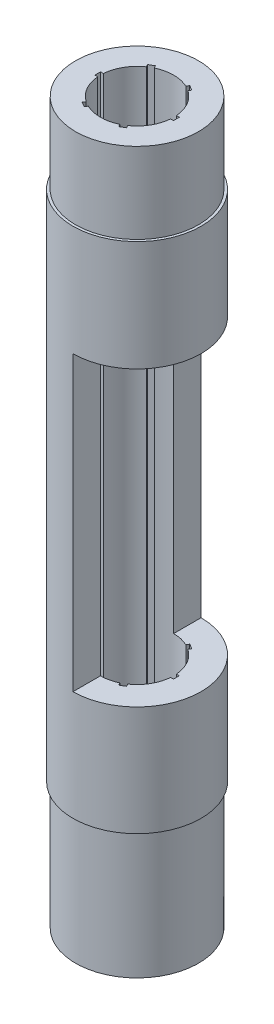
SolidWorks part; units mm, degrees
ref_plane "Front Plane" through (0, 0, 0) normal (0, 0, 1) x (1, 0, 0)
ref_plane "Top Plane" through (0, 0, 0) normal (0, 1, 0) x (1, 0, 0)
ref_plane "Right Plane" through (0, 0, 0) normal (1, 0, 0) x (0, 0, -1)
sketch "Sketch1" plane through (0, 0, 0) normal (0, 1, 0) x (1, 0, 0)
  circle A0 centre (0, 0) radius 11.1125
  circle A1 centre (0, 0) radius 6.35
  dimension "D1" = 12.7
  dimension "D2" = 22.225
extrude "Boss-Extrude1" add sketch "Sketch1" along normal blind 125
sketch "Sketch2" plane through (0, 125, 0) normal (0, 1, 0) x (1, 0, 0)
  circle A0 centre (0, 0) radius 10.668
  circle A1 centre (0, 0) radius 11.1125 construction
  circle A2 centre (0, 0) radius 11.1125
  dimension "D1" = 21.336
extrude "Cut-Extrude1" cut sketch "Sketch2" against normal blind 14
sketch "Sketch3" plane through (0, 0, 0) normal (0, -1, 0) x (1, 0, 0)
  circle A0 centre (0, 0) radius 10.668 construction
  circle A1 centre (0, 0) radius 11.1125 construction
  circle A2 centre (0, 0) radius 10.668
  circle A3 centre (0, 0) radius 11.1125
extrude "Cut-Extrude2" cut sketch "Sketch3" against normal blind 22
sketch "Sketch4" plane through (0, 0, 0) normal (0, 0, 1) x (1, 0, 0)
  line L0 (11.1125, 22) -> (11.1125, 111) construction
  line L1 (11.1125, 91.85) -> (0, 91.85)
  line L2 (11.1125, 91.85) -> (11.1125, 41.05)
  line L3 (11.1125, 41.05) -> (0, 41.05)
  line L4 (0, 91.85) -> (0, 41.05)
  line L5 (-10.668, 22) -> (10.668, 22) construction
  dimension "D1" = 50.8
  dimension "D2" = 19.05
extrude "Cut-Extrude3" cut sketch "Sketch4" against normal through all both and the other way through all
sketch "Sketch6" plane through (0, 0, 0) normal (0, -1, 0) x (1, 0, 0)
  line L1 (-6.3303, -0.5) -> (-6.8303, -0.5)
  line L2 (-6.3303, -0.5) -> (-6.3303, 0.5)
  line L3 (-6.3303, 0.5) -> (-6.8303, 0.5)
  line L4 (-6.8303, -0.5) -> (-6.8303, 0.5)
  circle A1 centre (0, 0) radius 6.35 construction
  dimension "D1" = 1
  dimension "D2" = 0.5
extrude "Cut-Extrude4" cut sketch "Sketch6" against normal through all
pattern_circular "CirPattern1" count 6 over 360 about axis through (0, 0, 0) along (0, 1, 0) of "Cut-Extrude4"
